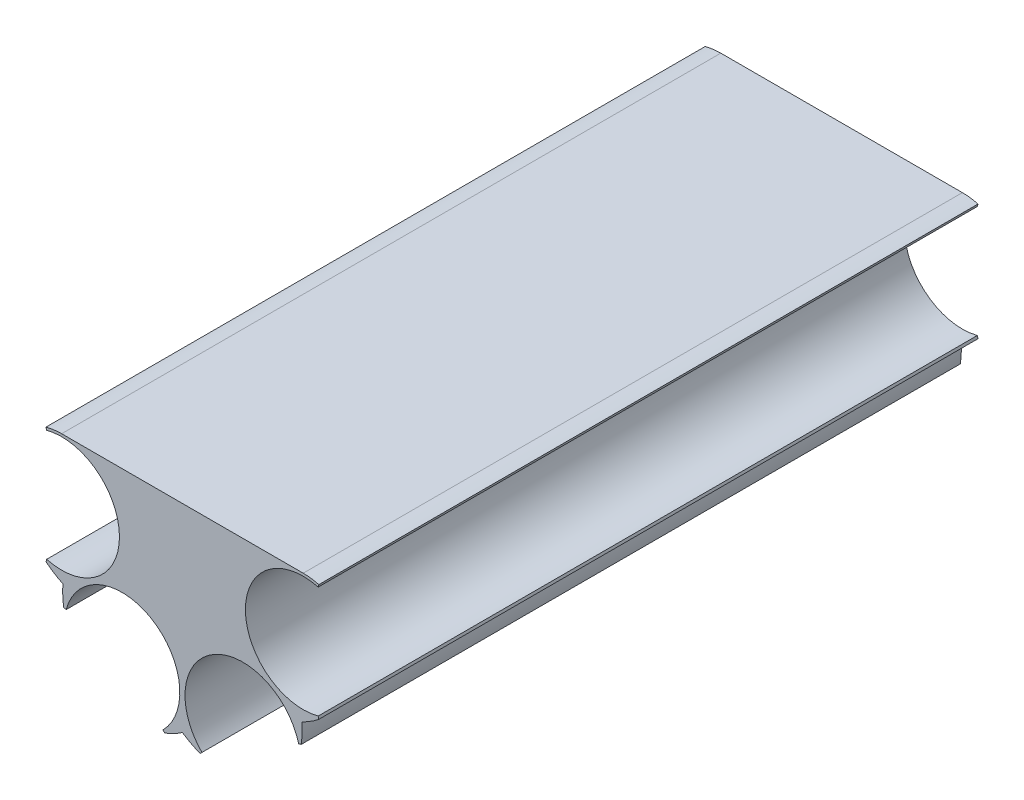
SolidWorks part; units mm, degrees
ref_plane "Plan de face" through (0, 0, 0) normal (0, 0, 1) x (1, 0, 0)
ref_plane "Plan de dessus" through (0, 0, 0) normal (0, 1, 0) x (1, 0, 0)
ref_plane "Plan de droite" through (0, 0, 0) normal (1, 0, 0) x (0, 0, -1)
sketch "Esquisse1" plane through (0, 0, 0) normal (0, 0, 1) x (1, 0, 0)
  line L0 (-35, 0) -> (35, 0) construction
  line L2 (0, 0) -> (0, -53.5) construction
  line L3 (-39.5293, 16.9037) -> (-39.3352, 16.1793)
  line L4 (-31.4635, 18.3063) -> (31.5363, 18.1806) construction
  line L5 (-31.4635, 18.3063) -> (-31.4137, 43.3063) construction
  line L6 (-31.4137, 43.3063) -> (31.5862, 43.1806) construction
  line L7 (31.5363, 18.1806) -> (31.5862, 43.1806) construction
  line L8 (-39.3352, 16.1793) -> (-35, 0) construction
  line L9 (-35, 0) -> (-39.3352, -16.1793) construction
  line L10 (-39.5293, -16.9037) -> (-39.3352, -16.1793)
  line L11 (-34.4037, -25.7816) -> (-33.6793, -25.9757)
  line L12 (-5.1256, -42.6853) -> (-5.656, -42.1549)
  line L13 (5.1256, -42.6853) -> (5.656, -42.1549)
  line L14 (34.4037, -25.7816) -> (33.6793, -25.9757)
  line L15 (39.5293, -16.9037) -> (39.3352, -16.1793)
  line L16 (39.5293, 16.9037) -> (39.3352, 16.1793)
  line L17 (-34.6353, -19.9967) -> (0, 0) construction
  line L18 (-35, 17.5) -> (35, 17.5)
  circle A0 centre (0, 0) radius 17.5 construction
  circle A1 centre (35, 0) radius 17.5 construction
  circle A2 centre (-35, 0) radius 17.5 construction
  circle A3 centre (-17.5, -30.3109) radius 17.5 construction
  circle A4 centre (17.5, -30.3109) radius 17.5 construction
  circle A6 centre (0, 0) radius 53.5 construction
  circle A7 centre (0, 0) radius 16.75 construction
  circle A8 centre (35, 0) radius 16.75 construction
  circle A9 centre (-35, 0) radius 16.75 construction
  circle A10 centre (-17.5, -30.3109) radius 16.75 construction
  circle A11 centre (17.5, -30.3109) radius 16.75 construction
  arc A12 (-39.3352, 16.1793) -> (-39.3352, -16.1793) centre (-35, 0) cw
  arc A13 (-33.6793, -25.9757) -> (-5.656, -42.1549) centre (-17.5, -30.3109) cw
  arc A14 (-39.5293, 16.9037) -> (-35, 17.5) centre (-35, 0) cw
  arc A15 (5.656, -42.1549) -> (33.6793, -25.9757) centre (17.5, -30.3109) cw
  arc A16 (39.3352, -16.1793) -> (39.3352, 16.1793) centre (35, 0) cw
  arc A17 (-39.5293, -16.9037) -> (-34.6353, -19.9967) centre (-23.8162, 2.541) ccw
  arc A18 (-34.4037, -25.7816) -> (-34.6353, -19.9967) centre (-9.7075, -21.896) cw
  arc A19 (-5.1256, -42.6853) -> (0, -39.9933) centre (-14.1087, -19.3549) ccw
  arc A20 (5.1256, -42.6853) -> (0, -39.9933) centre (14.1087, -19.3549) cw
  arc A21 (34.4037, -25.7816) -> (34.6353, -19.9967) centre (9.7075, -21.896) ccw
  arc A22 (39.5293, -16.9037) -> (34.6353, -19.9967) centre (23.8162, 2.541) cw
  arc A23 (39.5293, 16.9037) -> (35, 17.5) centre (35, 0) ccw
  point P48 (0, 0)
  point P61 (0, 0)
  dimension "D1" = 35
  dimension "D5" = 33.5
  dimension "D6" = 32.3585
  dimension "D7" = 150
  dimension "D8" = 4
  dimension "D9" = 20
  dimension "D10" = 3
  dimension "D11" = 25
  dimension "D12" = 17.5
  dimension "D3" = 63
  dimension "D4" = 25
extrude "Boss.-Extru.1" add sketch "Esquisse1" along normal blind 191
